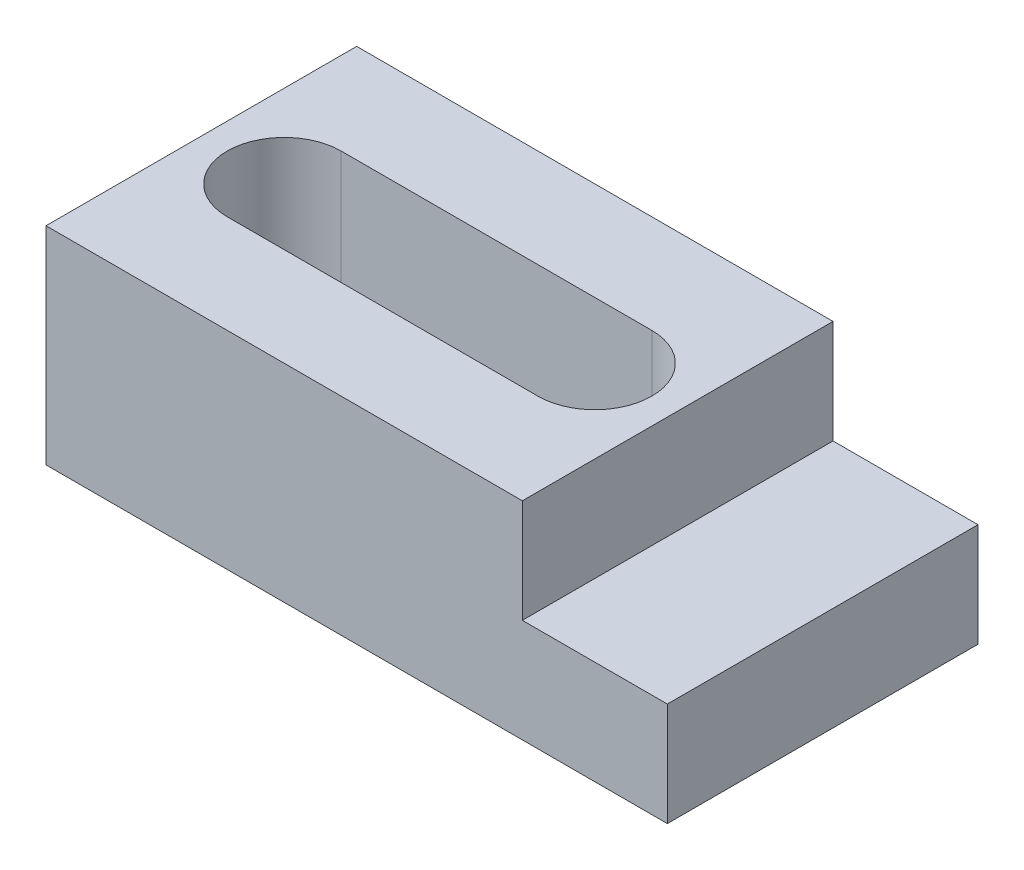
SolidWorks part; units mm, degrees
ref_plane "Front Plane" through (0, 0, 0) normal (0, 0, 1) x (1, 0, 0)
ref_plane "Top Plane" through (0, 0, 0) normal (0, 1, 0) x (1, 0, 0)
ref_plane "Right Plane" through (0, 0, 0) normal (1, 0, 0) x (0, 0, -1)
sketch "Sketch1" plane through (0, 0, 0) normal (0, 1, 0) x (1, 0, 0)
  line L0 (15, 0) -> (-15, 0) construction
  line L1 (-15, -7.5) -> (15, -7.5)
  line L2 (-15, -7.5) -> (-15, 7.5)
  line L3 (-15, 7.5) -> (15, 7.5)
  line L4 (15, -7.5) -> (15, 7.5)
  line L5 (-15, -7.5) -> (15, 7.5) construction
  line L6 (-15, 7.5) -> (15, -7.5) construction
  line L10 (7.5, 7.5) -> (7.5, -7.5) construction
  line L11 (-11, 2.75) -> (4, 2.75)
  line L12 (-11, -2.75) -> (4, -2.75)
  arc A0 (-11, 2.75) -> (-11, -2.75) centre (-11, 0) ccw
  arc A2 (4, -2.75) -> (4, 2.75) centre (4, 0) ccw
  point P0 (0, 0)
  dimension "D6" = 5.5
  dimension "D1" = 15
  dimension "D2" = 7.5
  dimension "D3" = 30
  dimension "D4" = 15
  dimension "D5" = 4
extrude "Boss-Extrude1" add sketch "Sketch1" along normal blind 10
sketch "Sketch2" plane through (0, 0, 7.5) normal (0, 0, 1) x (1, 0, 0)
  line L1 (15, 10) -> (8, 10)
  line L2 (15, 10) -> (15, 5)
  line L3 (15, 5) -> (8, 5)
  line L4 (8, 10) -> (8, 5)
  dimension "D1" = 7
  dimension "D2" = 5
extrude "Cut-Extrude1" cut sketch "Sketch2" against normal through all both and the other way through all
